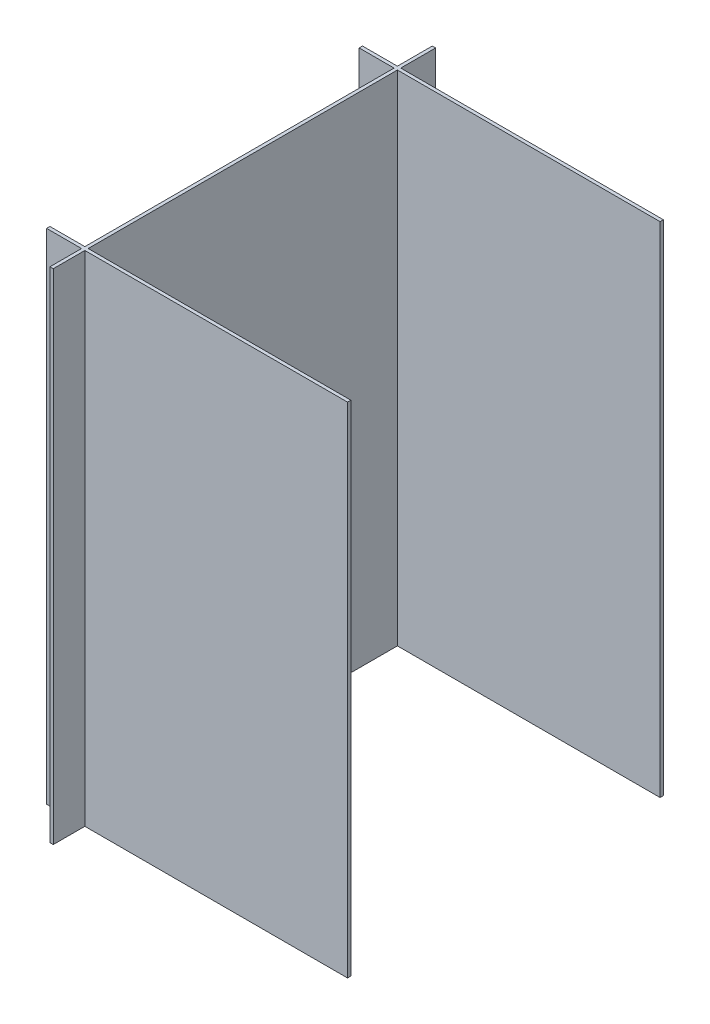
SolidWorks part; units mm, degrees
ref_plane "Front Plane" through (0, 0, 0) normal (0, 0, 1) x (1, 0, 0)
ref_plane "Top Plane" through (0, 0, 0) normal (0, 1, 0) x (1, 0, 0)
ref_plane "Right Plane" through (0, 0, 0) normal (1, 0, 0) x (0, 0, -1)
sketch "Sketch1" plane through (0, 0, 0) normal (0, 1, 0) x (1, 0, 0)
  line L0 (-56.1616, -42.3023) -> (-35.1616, -42.3023)
  line L1 (-33.1616, -42.3023) -> (124.8384, -42.3023)
  line L2 (-56.1616, -232.3023) -> (-35.1616, -232.3023)
  line L3 (-33.1616, -232.3023) -> (124.8384, -232.3023)
  line L4 (-35.1616, -42.3023) -> (-35.1616, -21.3023)
  line L5 (-33.1616, -42.3023) -> (-33.1616, -21.3023)
  line L6 (-35.1616, -232.3023) -> (-35.1616, -251.3023)
  line L7 (-33.1616, -232.3023) -> (-33.1616, -251.3023)
  line L8 (-56.1616, -44.3023) -> (-35.1616, -44.3023)
  line L9 (-33.1616, -44.3023) -> (124.8384, -44.3023)
  line L10 (-33.1616, -44.3023) -> (-33.1616, -230.3023)
  line L11 (-33.1616, -230.3023) -> (124.8384, -230.3023)
  line L12 (124.8384, -230.3023) -> (124.8384, -232.3023)
  line L13 (-56.1616, -42.3023) -> (-56.1616, -44.3023)
  line L14 (-35.1616, -44.3023) -> (-35.1616, -230.3023)
  line L15 (-35.1616, -230.3023) -> (-56.1616, -230.3023)
  line L16 (-56.1616, -230.3023) -> (-56.1616, -232.3023)
  line L17 (124.8384, -42.3023) -> (124.8384, -44.3023)
  line L18 (-35.1616, -21.3023) -> (-33.1616, -21.3023)
  line L20 (-35.1616, -251.3023) -> (-33.1616, -251.3023)
  dimension "D1" = 190
  dimension "D2" = 2
  dimension "D3" = 2
  dimension "D4" = 2
  dimension "D5" = 2
  dimension "D6" = 21
  dimension "D7" = 21
  dimension "D8" = 160
  dimension "D9" = 23
extrude "Boss-Extrude1" add sketch "Sketch1" along normal blind 300
